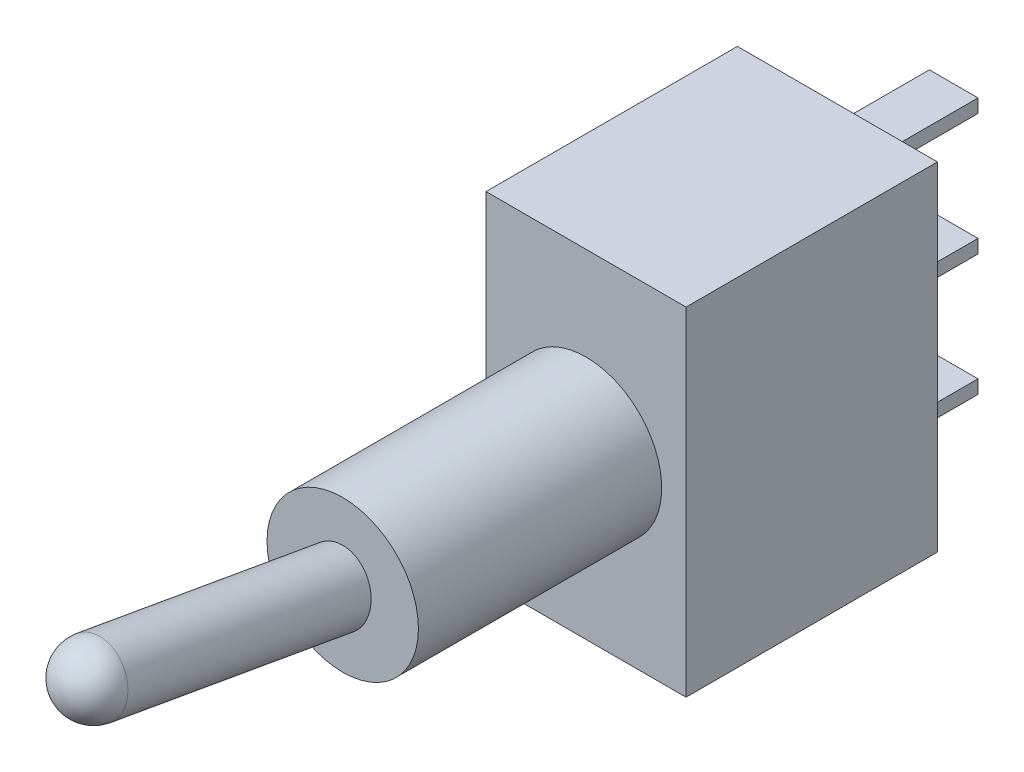
SolidWorks part; units mm, degrees
ref_plane "Plan de face" through (0, 0, 0) normal (0, 0, 1) x (1, 0, 0)
ref_plane "Plan de dessus" through (0, 0, 0) normal (0, 1, 0) x (1, 0, 0)
ref_plane "Plan de droite" through (0, 0, 0) normal (1, 0, 0) x (0, 0, -1)
sketch "Esquisse1" plane through (0, 0, 0) normal (0, 0, 1) x (1, 0, 0)
  line L1 (0, 0) -> (7.4, 0)
  line L2 (0, 0) -> (0, 12.5)
  line L3 (0, 12.5) -> (7.4, 12.5)
  line L4 (7.4, 0) -> (7.4, 12.5)
  dimension "D1" = 7.4
  dimension "D2" = 12.5
extrude "Boss.-Extru.1" add sketch "Esquisse1" along normal blind 9.3
sketch "Esquisse2" plane through (0, 0, 0) normal (0, 0, -1) x (-1, 0, 0)
  line L0 (-3.7, 0) -> (-3.7, 1.5) construction
  line L1 (-2.8, 1.5) -> (-4.6, 1.5)
  line L2 (-2.8, 1.5) -> (-2.8, 2)
  line L3 (-2.8, 2) -> (-4.6, 2)
  line L4 (-4.6, 1.5) -> (-4.6, 2)
  line L5 (-2.8, 6) -> (-4.6, 6)
  line L6 (-2.8, 6) -> (-2.8, 6.5)
  line L7 (-2.8, 6.5) -> (-4.6, 6.5)
  line L8 (-4.6, 6) -> (-4.6, 6.5)
  line L9 (-2.8, 10.5) -> (-4.6, 10.5)
  line L10 (-2.8, 10.5) -> (-2.8, 11)
  line L11 (-2.8, 11) -> (-4.6, 11)
  line L12 (-4.6, 10.5) -> (-4.6, 11)
  line L13 (0, 0) -> (-7.4, 0) construction
  line L14 (0, 6.25) -> (-2.8, 6.25) construction
  line L15 (0, 12.5) -> (0, 0) construction
  line L16 (-3.7, 12.5) -> (-3.7, 11) construction
  line L17 (-7.4, 12.5) -> (0, 12.5) construction
  line L18 (-3.7, 10.5) -> (-3.7, 6.5) construction
  line L19 (-3.7, 6) -> (-3.7, 2) construction
  dimension "D1" = 1.8
  dimension "D2" = 0.5
  dimension "D3" = 1.5
extrude "Boss.-Extru.2" add sketch "Esquisse2" along normal blind 4.3
sketch "Esquisse3" plane through (0, 0, 9.3) normal (0, 0, 1) x (1, 0, 0)
  circle A0 centre (3.7, 6.25) radius 2.8
  dimension "D1" = 5.6
extrude "Boss.-Extru.3" add sketch "Esquisse3" along normal blind 9
ref_plane "Plan1" through (3.7, 0, 0) normal (1, 0, 0) x (0, 0, -1)
sketch "Esquisse4" plane through (3.7, 0, 0) normal (1, 0, 0) x (0, 0, -1)
  line L0 (-18.3, 6.25) -> (-26.802, 6.25) construction
  line L1 (-18.3, 9.05) -> (-18.3, 3.45) construction
  line L2 (-18.3, 6.25) -> (-27.8707, 7.9376) construction
  line L3 (-18.3, 6.25) -> (-18.3, 7.5193)
  line L4 (-18.3, 7.5193) -> (-27.3, 9.1062)
  line L5 (-18.3, 6.25) -> (-28.7481, 8.0923)
  arc A0 (-27.3, 9.1062) -> (-28.7481, 8.0923) centre (-27.5171, 7.8752) ccw
  dimension "D1" = 10
  dimension "D2" = 9
  dimension "D3" = 1.25
revolve "Révolution1" add sketch "Esquisse4" angle 360 about L5
